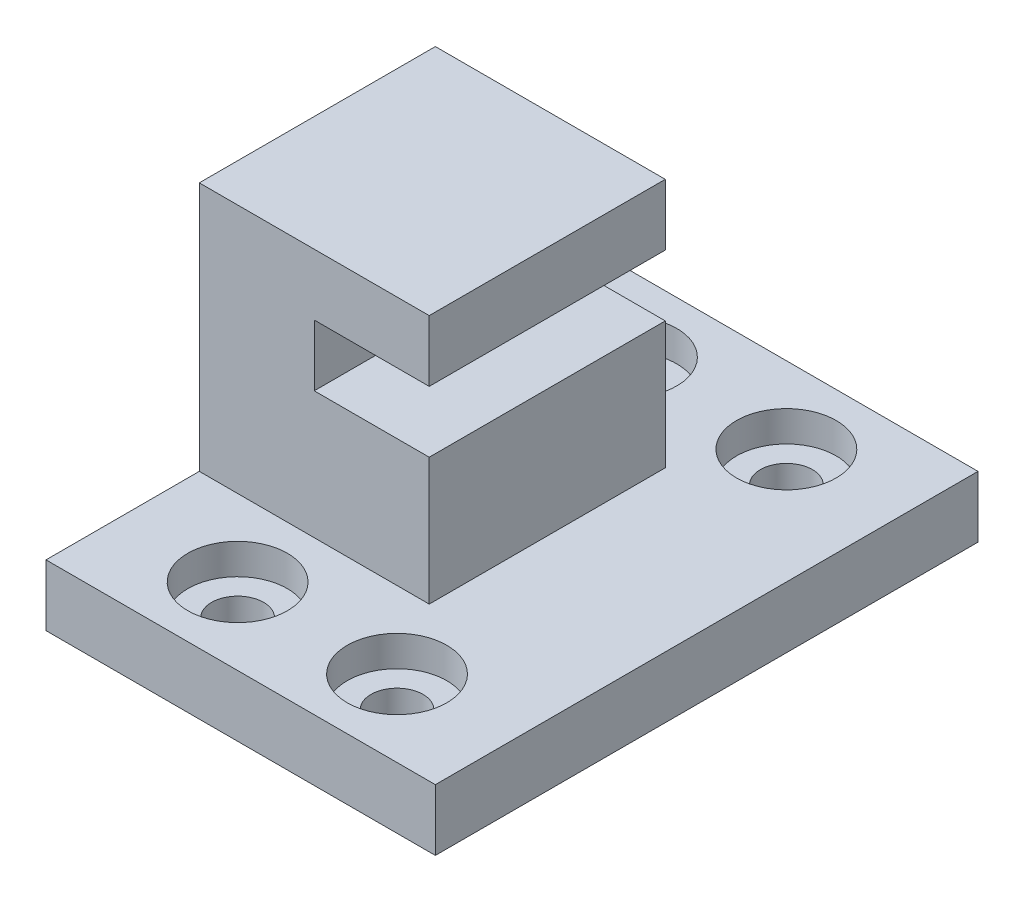
SolidWorks part; units mm, degrees
ref_plane "Front Plane" through (0, 0, 0) normal (0, 0, 1) x (1, 0, 0)
ref_plane "Top Plane" through (0, 0, 0) normal (0, 1, 0) x (1, 0, 0)
ref_plane "Right Plane" through (0, 0, 0) normal (1, 0, 0) x (0, 0, -1)
sketch "Croquis1" plane through (0, 0, 0) normal (0, 1, 0) x (1, 0, 0)
  line L0 (-12.7, -17.7) -> (-12.7, 17.7)
  line L1 (-5.2, -10.2) -> (5.2, -10.2)
  line L2 (-5.2, -10.2) -> (-5.2, 10.2)
  line L3 (-5.2, 10.2) -> (5.2, 10.2)
  line L4 (5.2, -10.2) -> (5.2, 10.2)
  line L5 (-5.2, -10.2) -> (5.2, 10.2) construction
  line L6 (-5.2, 10.2) -> (5.2, -10.2) construction
  line L7 (-12.7, 17.7) -> (12.7, 17.7)
  line L8 (12.7, -17.7) -> (12.7, 17.7)
  line L9 (-12.7, -17.7) -> (12.7, -17.7)
  point P0 (0, 0)
  dimension "D1" = 10.4
  dimension "D2" = 20.4
  dimension "D3" = 7.5
extrude "Saliente-Extruir1" add sketch "Croquis1" along normal blind 4 contours L1 L4 L3 L2
sketch "Croquis2" plane through (0, 0, 0) normal (0, 1, 0) x (1, 0, 0)
  line L0 (-12.7, -17.7) -> (12.7, -17.7) construction
  line L1 (12.7, -17.7) -> (12.7, 17.7) construction
  line L2 (-12.7, 17.7) -> (12.7, 17.7) construction
  line L3 (-12.7, -17.7) -> (-12.7, 17.7) construction
  line L4 (-12.7, -17.7) -> (12.7, -17.7)
  line L5 (12.7, -17.7) -> (12.7, 17.7)
  line L6 (-12.7, 17.7) -> (12.7, 17.7)
  line L7 (-12.7, -17.7) -> (-12.7, 17.7)
extrude "Saliente-Extruir2" add sketch "Croquis2" along normal blind 4
sketch "Croquis3" plane through (0, 4, 0) normal (0, 1, 0) x (1, 0, 0)
  line L1 (-12.7, 7.7) -> (2.3, 7.7)
  line L2 (-12.7, 7.7) -> (-12.7, -7.7)
  line L3 (-12.7, -7.7) -> (2.3, -7.7)
  line L4 (2.3, 7.7) -> (2.3, -7.7)
  line L5 (-12.7, 17.7) -> (-12.7, -17.7) construction
  line L6 (-12.7, -17.7) -> (12.7, -17.7) construction
  line L7 (12.7, 17.7) -> (-12.7, 17.7) construction
  dimension "D1" = 15
  dimension "D2" = 10
  dimension "D3" = 10
extrude "Saliente-Extruir3" add sketch "Croquis3" along normal blind 16.3
sketch "Croquis4" plane through (0, 0, 7.7) normal (0, 0, 1) x (1, 0, 0)
  line L0 (2.3, 20.3) -> (2.3, 4) construction
  line L1 (2.3, 16.3) -> (-5.2, 16.3)
  line L2 (2.3, 16.3) -> (2.3, 12.3)
  line L3 (2.3, 12.3) -> (-5.2, 12.3)
  line L4 (-5.2, 16.3) -> (-5.2, 12.3)
  line L5 (-12.7, 20.3) -> (2.3, 20.3) construction
  dimension "D1" = 7.5
  dimension "D2" = 4
  dimension "D3" = 4
extrude "Cortar-Extruir1" cut sketch "Croquis4" against normal through all
sketch "Croquis5" plane through (0, 4, 0) normal (0, 1, 0) x (1, 0, 0)
  line L0 (-12.7, 12.7) -> (12.7, 12.7) construction
  line L1 (-12.7, 17.7) -> (-12.7, 7.7) construction
  line L2 (12.7, -17.7) -> (12.7, 17.7) construction
  line L3 (-12.7, -12.7) -> (12.7, -12.7) construction
  line L4 (-12.7, -7.7) -> (-12.7, -17.7) construction
  line L5 (-5.2, 17.7) -> (-5.2, -17.7) construction
  line L6 (12.7, 17.7) -> (-12.7, 17.7) construction
  line L7 (-12.7, -17.7) -> (12.7, -17.7) construction
  line L9 (0, -11.165) -> (0, 11.165) construction
  line L10 (5.2, 17.7) -> (5.2, -17.7) construction
  line L12 (-12.7, 17.7) -> (12.7, -17.7) construction
  point P20 (-5.2, 12.7)
  point P21 (7.5, 12.7)
  point P22 (5.2, -12.7)
  point P23 (-5.2, -12.7)
  dimension "D1" = 7.5
hole_wizard "Refrentado para tornillo con cabeza plana de M32" positions "Croquis9" profile "Croquis10" counterbore size "M3" standard "DIN" end condition through all
sketch "Croquis9" plane through (0, 4, 0) normal (0, 1, 0) x (1, 0, 0)
  line L0 (-12.7, 12.7) -> (12.7, 12.7) construction
  point P0 (-5.2, 12.7)
  point P3 (-5.2, -12.7)
  point P6 (5.2, -12.7)
  point P9 (5.2, 12.7)
sketch "Croquis10" plane through (-5.2, 4, -12.7) normal (1, 0, 0) x (0, 0, 1)
  line L0 (0, 0) -> (0, 4)
  line L1 (0, 4) -> (1.7, 4)
  line L3 (1.7, 4) -> (1.7, 2)
  line L4 (1.7, 2) -> (3.25, 2)
  line L5 (3.25, 2) -> (3.25, 0)
  line L7 (3.25, 0) -> (0, 0)
  line L11 (0, -6.35) -> (0, 107.95) construction
  dimension "Diámetro de taladro hasta el siguiente" = 3.4
  dimension "Profundidad de taladro hasta el siguiente" = 4
  dimension "Diámetro de refrentado" = 6.5
  dimension "Profundidad de refrentado" = 2
